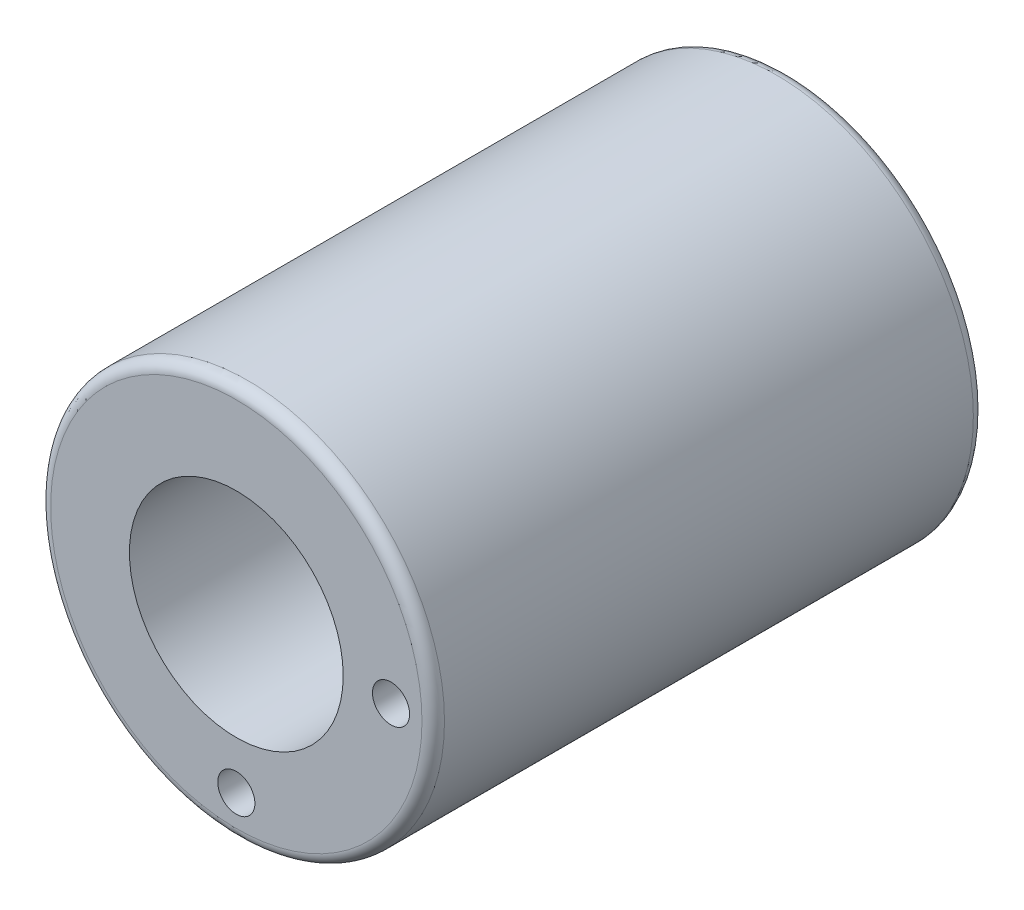
SolidWorks part; units mm, degrees
material "AISI 1020"
ref_plane "Plano frontal" through (0, 0, 0) normal (0, 0, 1) x (1, 0, 0)
ref_plane "Plano superior" through (0, 0, 0) normal (0, 1, 0) x (1, 0, 0)
ref_plane "Plano direito" through (0, 0, 0) normal (1, 0, 0) x (0, 0, -1)
sketch "Esboço1" plane through (0, 0, 0) normal (0, 0, 1) x (1, 0, 0)
  circle A0 centre (0, 0) radius 17.5
  circle A1 centre (0, 0) radius 9.5
  dimension "D1" = 35
  dimension "D2" = 8
extrude "Ressalto-extrusão1" add sketch "Esboço1" along normal mid plane 49
fillet "Filete1" radius 1 2 edges at (17.5, 0, 24.5) (17.5, 0, -24.5)
sketch "Esboço2" plane through (0, 0, 0) normal (1, 0, 0) x (0, 0, -1)
  circle A0 centre (0, 0) radius 6.5
  dimension "D1" = 13
extrude "Corte-extrusão1" cut sketch "Esboço2" against normal through all
hole_wizard "Furo roscado de M41" positions "Esboço3" profile "Esboço4" tap size "M4" standard "ISO"
sketch "Esboço3" plane through (0, 0, 24.5) normal (0, 0, 1) x (1, 0, 0)
  line L0 (0, -13.75) -> (0, 0) construction
  line L1 (0, 0) -> (13.75, 0) construction
  point P0 (13.75, 0)
  point P2 (0, -13.75)
  dimension "D1" = 13.75
sketch "Esboço4" plane through (13.75, 0, 24.5) normal (1, 0, 0) x (0, -1, 0)
  line L0 (0, 0) -> (0, 10.9914)
  line L1 (0, 10.9914) -> (1.65, 10)
  line L2 (1.65, 10) -> (1.65, 0)
  line L5 (1.65, 0) -> (0, 0)
  line L10 (0, 10.9914) -> (-1.65, 10) construction
  line L11 (0, -6.35) -> (0, 107.95) construction
  dimension "Tap Drill Dia." = 3.3
  dimension "Tap Drill Depth" = 10
  dimension "Drill Angle" = 118
cosmetic thread "Rosca de furo1" parameters "D1"=8, "D2"=4
cosmetic thread "Rosca de furo2" parameters "D1"=8, "D2"=4
